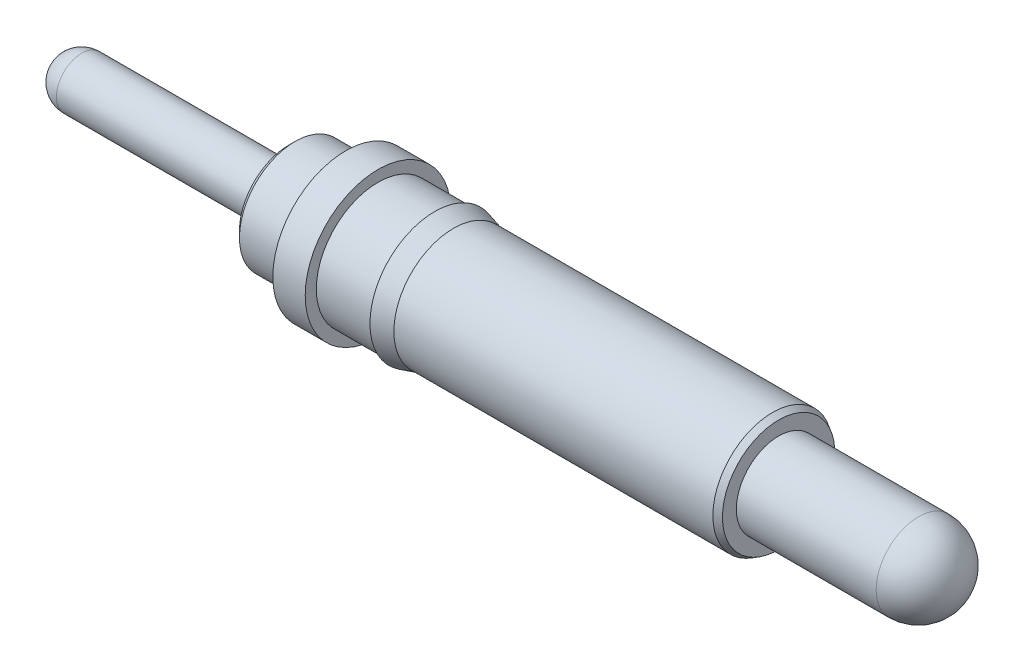
SolidWorks part; units mm, degrees
material "Brass Alloy 385"
ref_plane "Front Plane" through (0, 0, 0) normal (0, 0, 1) x (1, 0, 0)
ref_plane "Top Plane" through (0, 0, 0) normal (0, 1, 0) x (1, 0, 0)
ref_plane "Right Plane" through (0, 0, 0) normal (1, 0, 0) x (0, 0, -1)
sketch "Sketch1" plane through (0, 0, 0) normal (0, 0, 1) x (1, 0, 0)
  line L0 (0, 0) -> (13.8006, 0) construction
  line L1 (0, 0) -> (11.3538, 0)
  line L4 (0.3175, 0.3175) -> (2.921, 0.3175)
  line L5 (2.921, 0.3175) -> (2.921, 0.6223)
  line L6 (2.921, 0.6223) -> (2.9972, 0.6985)
  line L7 (2.9972, 0.6985) -> (3.6322, 0.6985)
  line L8 (3.6322, 0.6985) -> (3.6322, 0.9144)
  line L9 (3.6322, 0.9144) -> (4.0386, 0.9144)
  line L10 (4.0386, 0.9144) -> (4.0386, 0.7747)
  line L11 (4.0386, 0.7747) -> (4.7498, 0.7747)
  line L12 (4.7498, 0.7747) -> (4.7498, 0.8128)
  line L13 (4.7498, 0.8128) -> (4.9868, 0.7493)
  line L14 (4.9868, 0.7493) -> (8.9916, 0.7493)
  line L15 (8.9916, 0.7493) -> (9.0678, 0.7053)
  line L16 (9.0678, 0.7053) -> (9.0678, 0.5309)
  line L17 (9.0678, 0.5309) -> (10.8229, 0.5309)
  arc A0 (11.3538, 0) -> (10.8229, 0.5309) centre (10.8229, 0) ccw
  arc A2 (0.3175, 0.3175) -> (0, 0) centre (0.3175, 0) ccw
  dimension "D1" = 0.3175
  dimension "D14" = 0.5309
  dimension "D2" = 0.635
  dimension "D3" = 1.397
  dimension "D4" = 1.8288
  dimension "D5" = 1.4986
  dimension "D6" = 1.0617
  dimension "D7" = 1.6256
  dimension "D8" = 1.5494
  dimension "D9" = 15
  dimension "D10" = 30
  dimension "D11" = 0.4064
  dimension "D12" = 0.7112
  dimension "D13" = 0.7112
  dimension "B" = 6.1468
  dimension "D15" = 2.921
  dimension "A" = 7.7216
  dimension "D17" = 0.0762
  dimension "D20" = 45
  dimension "D21" = 0.0762
revolve "Revolve1" add sketch "Sketch1" angle 360 about L0
